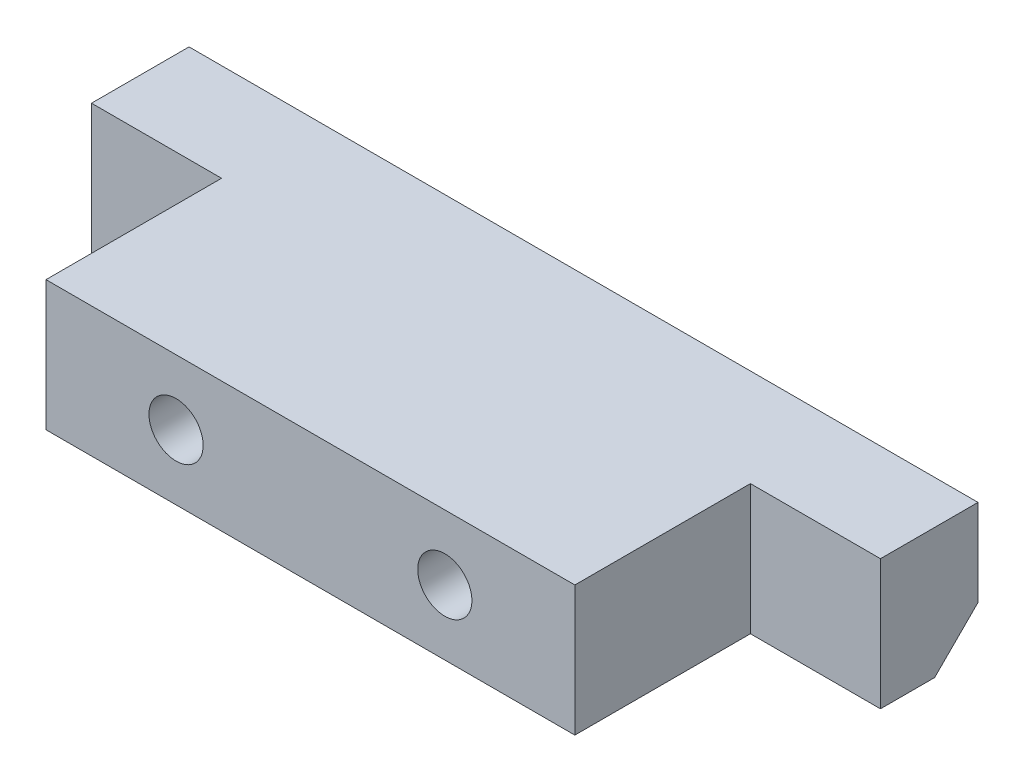
SolidWorks part; units mm, degrees
ref_plane "Plano frontal" through (0, 0, 0) normal (0, 0, 1) x (1, 0, 0)
ref_plane "Plano superior" through (0, 0, 0) normal (0, 1, 0) x (1, 0, 0)
ref_plane "Plano direito" through (0, 0, 0) normal (1, 0, 0) x (0, 0, -1)
sketch "Esboço1" plane through (0, 0, 0) normal (0, 0, 1) x (1, 0, 0)
  line L0 (-12.2, 0) -> (12.2, 0)
  line L1 (-12.2, 6) -> (12.2, 6)
  line L2 (0, 0) -> (0, 6) construction
  line L3 (-12.2, 0) -> (-12.2, 6)
  line L4 (12.2, 0) -> (12.2, 6)
  dimension "D2" = 24.4
  dimension "D3" = 6
extrude "Ressalto-extrusão1" add sketch "Esboço1" along normal blind 8.1
sketch "Esboço3" plane through (0, 0, 0) normal (0, 0, -1) x (-1, 0, 0)
  line L0 (-18.2, 0) -> (18.2, 0) construction
  line L1 (-12.2, 6) -> (12.2, 6) construction
  line L2 (-18.2, 0) -> (18.2, 0)
  line L3 (-18.2, 0) -> (-18.2, 6)
  line L4 (-18.2, 6) -> (18.2, 6)
  line L5 (18.2, 0) -> (18.2, 6)
  dimension "D1" = 36.4
extrude "Ressalto-extrusão2" add sketch "Esboço3" along normal blind 4.5
chamfer "Chanfro1" distance 2 distance2 2 1 edges at (0, 0, -4.5)
sketch "Esboço4" plane through (0, 0, 8.1) normal (0, 0, 1) x (1, 0, 0)
  line L0 (-12.2, 3) -> (12.2, 3) construction
  line L1 (-12.2, 6) -> (-12.2, 0) construction
  line L2 (12.2, 0) -> (12.2, 6) construction
  point P6 (-6.2, 3)
  point P7 (6.2, 3)
  dimension "D1" = 6
  dimension "D2" = 6
hole_wizard "Furo roscado de M3x0.51" positions "Esboço6" profile "Esboço5" tap size "M3x0.5" standard "Ansi Metric"
sketch "Esboço6" plane through (0, 0, 8.1) normal (0, 0, 1) x (1, 0, 0)
  point P0 (-6.2, 3)
  point P3 (6.2, 3)
sketch "Esboço5" plane through (-6.2, 3, 8.1) normal (1, 0, 0) x (0, -1, 0)
  line L0 (0, 0) -> (0, 9.2511)
  line L1 (0, 9.2511) -> (1.25, 8.5)
  line L2 (1.25, 8.5) -> (1.25, 0)
  line L5 (1.25, 0) -> (0, 0)
  line L10 (0, 9.2511) -> (-1.25, 8.5) construction
  line L11 (0, -6.35) -> (0, 107.95) construction
  dimension "Tap Drill Dia." = 2.5
  dimension "Tap Drill Depth" = 8.5
  dimension "Drill Angle" = 118
